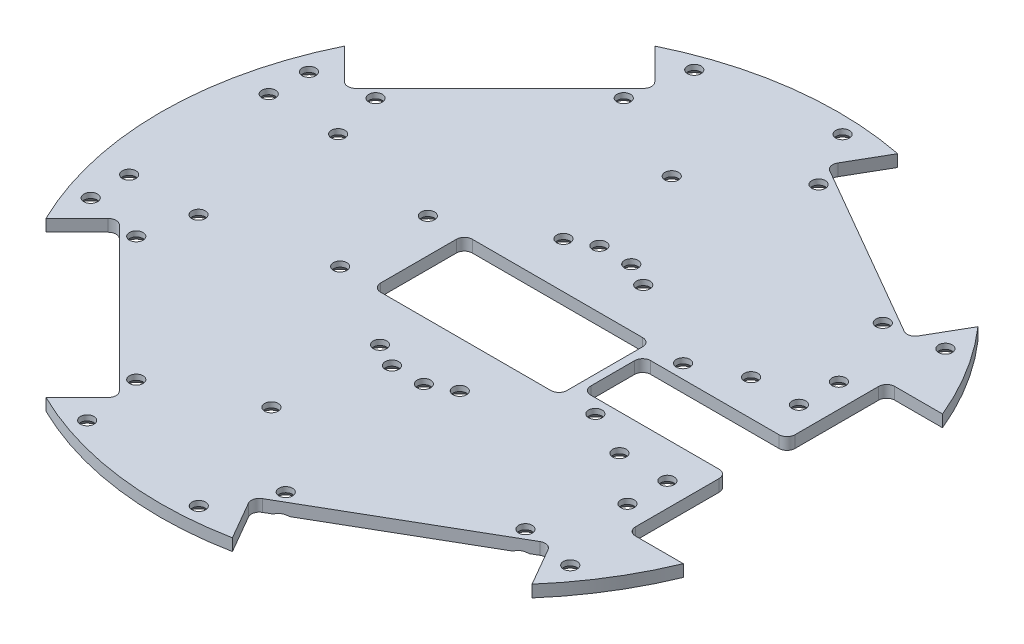
SolidWorks part; units mm, degrees
material "Liga 6061"
ref_plane "Plano frontal" through (0, 0, 0) normal (0, 0, 1) x (1, 0, 0)
ref_plane "Plano superior" through (0, 0, 0) normal (0, 1, 0) x (1, 0, 0)
ref_plane "Plano direito" through (0, 0, 0) normal (1, 0, 0) x (0, 0, -1)
sketch "Esboço1" plane through (0, 0, 0) normal (0, 1, 0) x (1, 0, 0)
  line L0 (0, -20.0389) -> (0, 0) construction
  line L1 (0, 0) -> (-50000, 0) construction
  line L2 (0, 0) -> (-35355.3391, -35355.3391) construction
  line L3 (-76.317, -37.4261) -> (-37.4261, -76.317) construction
  line L4 (16.3986, -83.4032) -> (64.03, -55.9032) construction
  line L5 (0, 0) -> (25000, -43301.2702) construction
  line L6 (16.3986, 83.4032) -> (64.03, 55.9032) construction
  line L7 (-76.317, 37.4261) -> (-37.4261, 76.317) construction
  line L8 (-61.1142, -30.0015) -> (-30.0015, -61.1142) construction
  line L9 (13.1617, -66.7968) -> (51.2668, -44.7968) construction
  line L10 (-67.1246, -28.2337) -> (-28.2337, -67.1246)
  line L15 (-67.1246, -28.2337) -> (-76.317, -37.4261)
  line L16 (-28.2337, -67.1246) -> (-37.4261, -76.317)
  line L17 (9.8986, -72.1448) -> (57.53, -44.6448)
  line L18 (64.03, -55.9032) -> (57.53, -44.6448)
  line L19 (16.3986, -83.4032) -> (9.8986, -72.1448)
  line L20 (64.03, 55.9032) -> (57.53, 44.6448)
  line L21 (9.8986, 72.1448) -> (57.53, 44.6448)
  line L22 (16.3986, 83.4032) -> (9.8986, 72.1448)
  line L23 (-28.2337, 67.1246) -> (-37.4261, 76.317)
  line L24 (-67.1246, 28.2337) -> (-28.2337, 67.1246)
  line L25 (-67.1246, 28.2337) -> (-76.317, 37.4261)
  line L28 (0, 0) -> (-75.1754, 27.3616) construction
  line L29 (-9.6973, 69) -> (0, 0) construction
  line L31 (0, 0) -> (64.7214, 47.0228) construction
  line L32 (3, 127.8652) -> (3, -125.0226) construction
  line L34 (0, 85) -> (0, 66.7968) construction
  arc A0 (-37.4261, -76.317) -> (16.3986, -83.4032) centre (0, 0) ccw
  arc A1 (64.03, -55.9032) -> (64.03, 55.9032) centre (0, 0) ccw
  arc A2 (-76.317, 37.4261) -> (-76.317, -37.4261) centre (0, 0) ccw
  arc A3 (16.3986, 83.4032) -> (-37.4261, 76.317) centre (0, 0) ccw
  circle A4 centre (-61.1142, -30.0015) radius 1.7
  circle A5 centre (-30.0015, -61.1142) radius 1.7
  circle A6 centre (13.1617, -66.7968) radius 1.7
  circle A7 centre (51.2668, -44.7968) radius 1.7
  circle A8 centre (-61.1142, 30.0015) radius 1.7
  circle A9 centre (-30.0015, 61.1142) radius 1.7
  circle A10 centre (13.1617, 66.7968) radius 1.7
  circle A11 centre (51.2668, 44.7968) radius 1.7
  circle A14 centre (-75.3985, 17.5) radius 1.5
  circle A15 centre (-58, 17.5) radius 1.5
  circle A16 centre (-58, -17.5) radius 1.5
  circle A17 centre (-75.3985, -17.5) radius 1.5
  circle A24 centre (-27.3176, 76.108) radius 1.5
  circle A32 centre (-75.1754, 27.3616) radius 1.5
  circle A33 centre (64.7214, 47.0228) radius 1.5
  circle A34 centre (64.7214, -47.0228) radius 1.5
  circle A35 centre (-75.1754, -27.3616) radius 1.5
  circle A36 centre (7, -26) radius 1.5
  circle A37 centre (13, -23) radius 1.5
  circle A38 centre (35, -11) radius 1.5
  circle A48 centre (5.2686, 80.7056) radius 1.5
  circle A49 centre (-7.0429, 50.1863) radius 1.5
  circle A50 centre (-27.3176, -76.108) radius 1.5
  circle A51 centre (5.2686, -80.7056) radius 1.5
  circle A52 centre (-7.0429, -50.1863) radius 1.5
  circle A53 centre (-29, -11) radius 1.5
  circle A54 centre (-7, -23) radius 1.5
  circle A55 centre (-1, -26) radius 1.5
  circle A56 centre (35, 11) radius 1.5
  circle A57 centre (13, 23) radius 1.5
  circle A58 centre (7, 26) radius 1.5
  circle A59 centre (-1, 26) radius 1.5
  circle A60 centre (-7, 23) radius 1.5
  circle A61 centre (-29, 11) radius 1.5
  point P6 (0, 0)
  point P13 (-56.8716, -56.8716)
  point P14 (51.2668, 44.7968)
  point P17 (40.2143, -69.6532)
  point P21 (-45.5579, -45.5579)
  point P24 (32.2143, -55.7968)
  point P25 (13.1617, 66.7968)
  point P26 (-30.0015, 61.1142)
  point P27 (-61.1142, 30.0015)
  point P42 (-27.3176, 76.108)
  point P48 (-47.6792, -47.6792)
  point P51 (33.7143, -58.3948)
  point P52 (-71.7208, -32.8299)
  point P57 (-71.7208, 32.8299)
  point P63 (-75.3985, 17.5)
  point P64 (-58, 17.5)
  point P73 (-9.6883, 68.9348)
  point P80 (-9.6973, 69)
  point P113 (-9.6973, 69)
  dimension "D1" = 170
  dimension "D6" = 3.4
  dimension "D12" = 7
  dimension "D17" = 3
  dimension "D18" = 3
  dimension "D11" = 3
  dimension "D14" = 58
  dimension "D10" = 3
  dimension "D22" = 3
  dimension "D23" = 3
  dimension "D24" = 3
  dimension "D25" = 3
  dimension "D26" = 3
  dimension "D29" = 26
  dimension "D30" = 4
  dimension "D31" = 10
  dimension "D32" = 32
  dimension "D2" = 45
  dimension "D3" = 55
  dimension "D4" = 30
  dimension "D5" = 44
  dimension "D7" = 69
  dimension "D8" = 82
  dimension "D9" = 19
  dimension "D13" = 17.3985
  dimension "D15" = 20
  dimension "D16" = 17.5
  dimension "D19" = 36
  dimension "D20" = 80
  dimension "D21" = 80
  dimension "D27" = 11
  dimension "D28" = 23
  dimension "D33" = 3
extrude "Base" add sketch "Esboço1" along normal blind 3
sketch "Esboço21" plane through (0, 0, 0) normal (0, -1, 0) x (1, 0, 0)
  line L0 (0, 0) -> (50000, 0) construction
  line L2 (64.5414, -32.5) -> (78.5414, -32.5)
  line L3 (64.5414, -32.5) -> (64.5414, 32.5)
  line L4 (64.5414, 32.5) -> (78.5414, 32.5)
  line L6 (64.5414, -32.5) -> (78.5414, 32.5) construction
  line L7 (64.5414, 32.5) -> (78.5414, -32.5) construction
  arc A0 (78.5414, 32.5) -> (78.5414, -32.5) centre (0, 0) cw
  circle A1 centre (58.5414, 26.5) radius 1.5
  circle A2 centre (58.5414, 16.5) radius 1.5
  circle A3 centre (46.5414, 16.5) radius 1.5
  circle A4 centre (46.5414, -16.5) radius 1.5
  circle A5 centre (58.5414, -16.5) radius 1.5
  circle A6 centre (58.5414, -26.5) radius 1.5
  point P3 (71.5414, 0)
  point P9 (58.5414, 26.5)
  point P10 (58.5414, 16.5)
  point P11 (46.5414, 16.5)
  dimension "D8" = 3
  dimension "D9" = 3
  dimension "D10" = 3
  dimension "D1" = 65
  dimension "D2" = 14
  dimension "D3" = 85
  dimension "D4" = 6
  dimension "D5" = 10
  dimension "D6" = 12
  dimension "D7" = 6
extrude "Boca Chute" cut sketch "Esboço21" against normal blind 20
sketch "Esboço32" plane through (64.5414, 0, 0) normal (1, 0, 0) x (0, 0, -1)
  line L0 (0, 7.9765) -> (0, -7.5498) construction
  line L1 (-32.5, 1.5) -> (32.5, 1.5) construction
  line L2 (-32.5, 3) -> (-32.5, 0) construction
  line L3 (32.5, 3) -> (32.5, 0) construction
  line L4 (32.5, 3) -> (-32.5, 3) construction
  line L5 (-7.5, 0) -> (7.5, 0)
  line L6 (-7.5, 0) -> (-7.5, 3)
  line L7 (-7.5, 3) -> (7.5, 3)
  line L8 (7.5, 0) -> (7.5, 3)
  line L9 (-7.5, 0) -> (7.5, 3) construction
  line L10 (-7.5, 3) -> (7.5, 0) construction
  point P9 (0, 1.5)
  dimension "D1" = 15
extrude "Corte-extrusão2" cut sketch "Esboço32" against normal blind 36.19
sketch "Esboço33" plane through (0, 3, 0) normal (0, 1, 0) x (1, 0, 0)
  line L0 (57.9822, 0) -> (-158.875, 0) construction
  line L1 (28.3514, 7.5) -> (28.3514, -7.5) construction
  line L2 (-20.3486, -11.5) -> (26.3514, -11.5)
  line L3 (-20.3486, -11.5) -> (-20.3486, 11.5)
  line L4 (-20.3486, 11.5) -> (26.3514, 11.5)
  line L5 (26.3514, -11.5) -> (26.3514, 11.5)
  line L6 (-20.3486, -11.5) -> (26.3514, 11.5) construction
  line L7 (-20.3486, 11.5) -> (26.3514, -11.5) construction
  point P1 (3.0014, 0)
  dimension "D1" = 2
  dimension "D2" = 46.7
  dimension "D3" = 23
extrude "Corte-extrusão3" cut sketch "Esboço33" against normal through all
hole_wizard "Escareado para SFHCS M31" positions "Esboço34" profile "Esboço35" countersink size "M3" standard "Ansi Metric" end condition through all
sketch "Esboço34" plane through (0, 0, 0) normal (0, -1, 0) x (-1, 0, 0)
  point P0 (-64.7214, 47.0228)
  point P3 (-58.5414, 26.5)
  point P6 (-58.5414, 16.5)
  point P9 (-51.2668, 44.7968)
  point P12 (-46.5414, 16.5)
  point P15 (-35, 11)
  point P18 (-13.1617, 66.7968)
  point P21 (-5.2686, 80.7056)
  point P24 (7.0429, 50.1863)
  point P27 (1, 26)
  point P30 (-7, 26)
  point P33 (-13, 23)
  point P36 (7, 23)
  point P39 (7.0429, 50.1863)
  point P41 (27.3176, 76.108)
  point P44 (30.0015, 61.1142)
  point P47 (29, 11)
  point P50 (61.1142, 30.0015)
  point P53 (58, 17.5)
  point P56 (75.3985, 17.5)
  point P59 (75.1754, 27.3616)
  point P62 (-35, -11)
  point P65 (-46.5414, -16.5)
  point P68 (-58.5414, -16.5)
  point P71 (-58.5414, -26.5)
  point P74 (-64.7214, -47.0228)
  point P77 (-51.2668, -44.7968)
  point P80 (-13.1617, -66.7968)
  point P83 (-5.2686, -80.7056)
  point P86 (7.0429, -50.1863)
  point P89 (-13, -23)
  point P92 (-7, -26)
  point P95 (1, -26)
  point P98 (7, -23)
  point P101 (30.0015, -61.1142)
  point P104 (27.3176, -76.108)
  point P107 (29, -11)
  point P110 (58, -17.5)
  point P113 (75.3985, -17.5)
  point P116 (75.1754, -27.3616)
  point P119 (61.1142, -30.0015)
sketch "Esboço35" plane through (64.7214, 0, -47.0228) normal (1, 0, 0) x (0, 0, -1)
  line L0 (0, 0) -> (0, 3)
  line L1 (0, 3) -> (1.7, 3)
  line L2 (1.7, 3) -> (1.7, 1.66)
  line L3 (1.7, 1.66) -> (3.36, 0)
  line L5 (3.36, 0) -> (0, 0)
  line L6 (-1.7, 1.66) -> (-3.36, 0) construction
  line L11 (0, -6.35) -> (0, 107.95) construction
  dimension "Thru Hole Dia." = 3.4
  dimension "Thru Hole Depth" = 3
  dimension "Near C'Sink Dia." = 6.72
  dimension "Near C'Sink Angle" = 90
fillet "Filete1" radius 2 18 edges at (26.3514, 1.5, 11.5) (26.3514, 1.5, -11.5) (-20.3486, 1.5, -11.5) (-20.3486, 1.5, 11.5) (64.5414, 1.5, 32.5) (64.5414, 1.5, -32.5) (64.5414, 1.5, 7.5) (64.5414, 1.5, -7.5) (28.3514, 1.5, 7.5) (28.3514, 1.5, -7.5) (9.8986, 1.5, -72.1448) (57.53, 1.5, -44.6448) (-67.1246, 1.5, -28.2337) (-28.2337, 1.5, -67.1246) (-67.1246, 1.5, 28.2337) (-28.2337, 1.5, 67.1246) (9.8986, 1.5, 72.1448) (57.53, 1.5, 44.6448)
